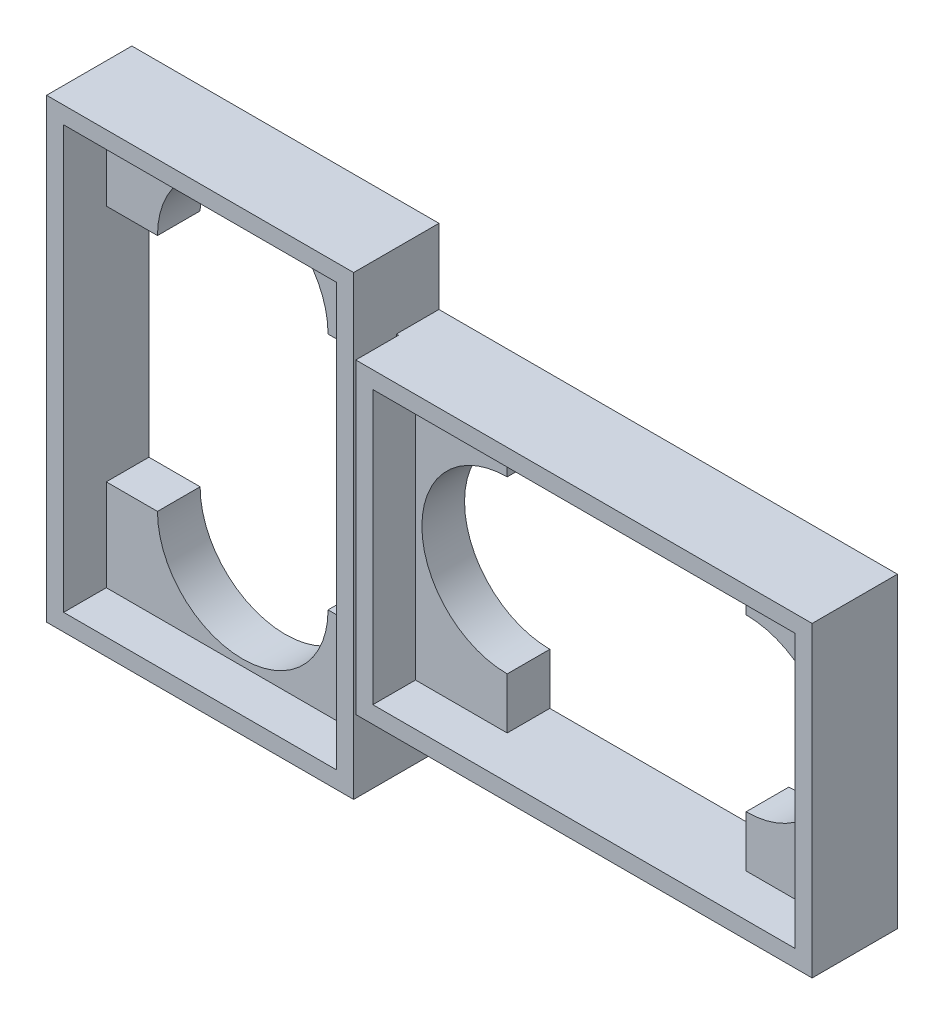
SolidWorks part; units mm, degrees
ref_plane "Front Plane" through (0, 0, 0) normal (0, 0, 1) x (1, 0, 0)
ref_plane "Top Plane" through (0, 0, 0) normal (0, 1, 0) x (1, 0, 0)
ref_plane "Right Plane" through (0, 0, 0) normal (1, 0, 0) x (0, 0, -1)
sketch "Sketch1" plane through (0, 0, 0) normal (0, 0, 1) x (1, 0, 0)
  line L1 (-50, -27.5) -> (50, -27.5)
  line L2 (-50, -27.5) -> (-50, 27.5)
  line L3 (-50, 27.5) -> (50, 27.5)
  line L4 (50, -27.5) -> (50, 27.5)
  line L5 (-50, -27.5) -> (50, 27.5) construction
  line L6 (-50, 27.5) -> (50, -27.5) construction
  point P0 (0, 0)
  dimension "D1" = 100
  dimension "D2" = 55
extrude "Boss-Extrude1" add sketch "Sketch1" along normal blind 5
sketch "Sketch2" plane through (0, 0, 5) normal (0, 0, 1) x (1, 0, 0)
  line L0 (0, 0) -> (-50, 0)
  line L1 (-50, 27.5) -> (-50, -27.5) construction
  line L2 (0, 0) -> (20, 0)
  line L3 (-7, -26.75) -> (-43, -26.75)
  line L4 (-7, -26.75) -> (-7, 26.75)
  line L5 (-7, 26.75) -> (-43, 26.75)
  line L6 (-43, -26.75) -> (-43, 26.75)
  line L7 (-7, -26.75) -> (-43, 26.75) construction
  line L8 (-7, 26.75) -> (-43, -26.75) construction
  line L10 (46.75, -18) -> (-6.75, -18)
  line L11 (46.75, -18) -> (46.75, 18)
  line L12 (46.75, 18) -> (-6.75, 18)
  line L13 (-6.75, -18) -> (-6.75, 18)
  line L14 (46.75, -18) -> (-6.75, 18) construction
  line L15 (46.75, 18) -> (-6.75, -18) construction
  point P5 (-25, 0)
  dimension "D1" = 20
  dimension "D2" = 53.5
  dimension "D3" = 36
  dimension "D4" = 53.5
  dimension "D5" = 36
extrude "Extrude-Thin3" add sketch "Sketch2" along normal blind 5 thin
sketch "Sketch3" plane through (0, 0, 5) normal (0, 0, 1) x (1, 0, 0)
  line L0 (-41, 0) -> (-9, 0)
  line L1 (-41, -24.75) -> (-41, 24.75) construction
  line L2 (-9, -24.75) -> (-9, 24.75) construction
  line L3 (-25, 24.75) -> (-25, -24.75)
  line L4 (-9, 24.75) -> (-41, 24.75) construction
  line L5 (-9, -24.75) -> (-41, -24.75) construction
  line L7 (-35, -14) -> (-15, -14)
  line L8 (-35, -14) -> (-35, 14)
  line L9 (-35, 14) -> (-15, 14)
  line L10 (-15, -14) -> (-15, 14)
  line L11 (-35, -14) -> (-15, 14) construction
  line L12 (-35, 14) -> (-15, -14) construction
  arc A0 (-35, 14) -> (-15, 14) centre (-25, 14) cw
  arc A1 (-15, -14) -> (-35, -14) centre (-25, -14) cw
  point P12 (-25, 0)
  dimension "D1" = 20
  dimension "D2" = 28
extrude "Cut-Extrude1" cut sketch "Sketch3" against normal blind 5 contours A0 L3 L9 | A0 L9 L3 | L9 L8 L0 L3 | L0 L10 L9 L3 | L7 L10 L0 L3 | L8 L7 L3 L0 | A1 L3 L7 | A1 L7 L3
sketch "Sketch4" plane through (0, 0, 5) normal (0, 0, 1) x (1, 0, 0)
  line L0 (20, 16) -> (20, -16)
  line L1 (44.75, 16) -> (-4.75, 16) construction
  line L2 (44.75, -16) -> (-4.75, -16) construction
  line L3 (-4.75, 0) -> (44.75, 0)
  line L4 (-4.75, -16) -> (-4.75, 16) construction
  line L5 (44.75, -16) -> (44.75, 16) construction
  line L7 (34, -10) -> (6, -10)
  line L8 (34, -10) -> (34, 10)
  line L9 (34, 10) -> (6, 10)
  line L10 (6, -10) -> (6, 10)
  line L11 (34, -10) -> (6, 10) construction
  line L12 (34, 10) -> (6, -10) construction
  arc A0 (6, -10) -> (6, 10) centre (6, 0) cw
  arc A1 (34, -10) -> (34, 10) centre (34, 0) ccw
  point P12 (20, 0)
  dimension "D1" = 28
  dimension "D2" = 20
extrude "Cut-Extrude2" cut sketch "Sketch4" against normal blind 5 contours L10 L3 L0 L9 | L8 L9 L0 L3 | L7 L8 L3 L0 | L10 L7 L0 L3 | A0 L10 L3 | A0 L3 L10 | L3 A1 L8 | L8 A1 L3
sketch "Sketch5" plane through (0, 0, 5) normal (0, 0, 1) x (1, 0, 0)
  line L0 (-9, -24.75) -> (-9, 24.75) construction
  line L1 (-15, 14) -> (-9, 14)
  line L2 (-15, 14) -> (-15, -14)
  line L3 (-15, -14) -> (-9, -14)
  line L4 (-9, 14) -> (-9, -14)
  line L5 (-41, -24.75) -> (-41, 24.75) construction
  line L6 (-35, 14) -> (-41, 14)
  line L7 (-35, 14) -> (-35, -14)
  line L8 (-35, -14) -> (-41, -14)
  line L9 (-41, 14) -> (-41, -14)
  line L10 (44.75, 16) -> (-4.75, 16) construction
  line L11 (6, 10) -> (34, 10)
  line L12 (6, 10) -> (6, 16)
  line L13 (6, 16) -> (34, 16)
  line L14 (34, 10) -> (34, 16)
  line L15 (44.75, -16) -> (-4.75, -16) construction
  line L16 (6, -10) -> (34, -10)
  line L17 (6, -10) -> (6, -16)
  line L18 (6, -16) -> (34, -16)
  line L19 (34, -10) -> (34, -16)
  dimension "D1" = 28
extrude "Cut-Extrude3" cut sketch "Sketch5" against normal blind 5
sketch "Sketch6" plane through (0, 0, 5) normal (0, 0, 1) x (1, 0, 0)
  line L0 (-50, -27.5) -> (50, -27.5) construction
  line L1 (-50, 27.5) -> (-40.5, 27.5)
  line L2 (-50, 27.5) -> (-50, -27.5)
  line L3 (-50, -27.5) -> (-40.5, -27.5)
  line L4 (-40.5, 27.5) -> (-40.5, -27.5)
  line L5 (-7, -26.75) -> (-7, 26.75) construction
  line L6 (50, -27.5) -> (-7, -27.5)
  line L7 (50, -27.5) -> (50, -15.189)
  line L8 (50, -15.189) -> (-7, -15.189)
  line L9 (-7, -27.5) -> (-7, -15.189)
  line L10 (-7, -26.75) -> (-43, -26.75) construction
  line L11 (50, 27.5) -> (46.75, 27.5)
  line L12 (50, 27.5) -> (50, -18)
  line L13 (50, -18) -> (46.75, -18)
  line L14 (46.75, 27.5) -> (46.75, -18)
  line L15 (-7, 26.75) -> (46.75, 26.75)
  line L16 (-7, 26.75) -> (-7, 18)
  line L17 (-7, 18) -> (46.75, 18)
  line L18 (46.75, 26.75) -> (46.75, 18)
  line L19 (-40.5, 27.5) -> (46.75, 27.5)
  line L20 (-40.5, 27.5) -> (-40.5, 26.75)
  line L21 (-40.5, 26.75) -> (46.75, 26.75)
  line L22 (46.75, 27.5) -> (46.75, 26.75)
  line L23 (-40.5, -27.5) -> (-7, -27.5)
  line L24 (-40.5, -27.5) -> (-40.5, -26.75)
  line L25 (-40.5, -26.75) -> (-7, -26.75)
  line L26 (-7, -27.5) -> (-7, -26.75)
  line M1 (46.75, -18) -> (-6.75, -18)
  line M2 (-6.75, -18) -> (-6.75, 18)
  line M3 (-6.75, 18) -> (46.75, 18)
  line M4 (46.75, 18) -> (46.75, -18)
  line M5 (-7, 26.75) -> (-7, -26.75)
  line M6 (-7, -26.75) -> (-43, -26.75)
  line M7 (-43, -26.75) -> (-43, 26.75)
  line M8 (-43, 26.75) -> (-7, 26.75)
  line M9 (50, -27.5) -> (50, 27.5)
  line M10 (50, 27.5) -> (-50, 27.5)
  line M11 (-50, 27.5) -> (-50, -27.5)
  line M12 (-50, -27.5) -> (50, -27.5)
extrude "Cut-Extrude4" cut sketch "Sketch6" against normal blind 10 contours L17 L14 L15 M5 M3 | L4 M10 M11 M12 M7 | L13 L8 L9 M9 M1 M2 M5 M12 | L14 L8 M10 M4 M9 | L9 L4 M12 M6 | L15 L14 L4 M8 M10
sketch "Sketch7" plane through (0, -15.189, 0) normal (0, 1, 0) x (1, 0, 0)
  line L1 (50, -5) -> (46.75, -5)
  line L2 (50, -5) -> (50, 0)
  line L3 (50, 0) -> (46.75, 0)
  line L4 (46.75, -5) -> (46.75, 0)
extrude "Cut-Extrude5" cut sketch "Sketch7" against normal blind 10
